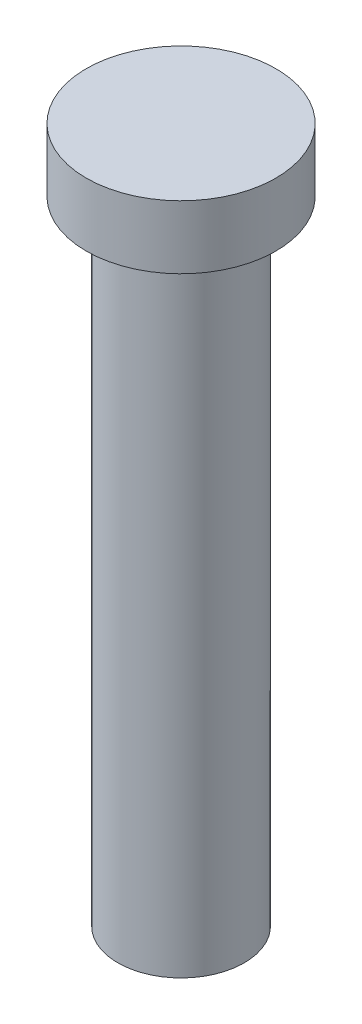
SolidWorks part; units mm, degrees
material "AISI 304"
ref_plane "前视基准面" through (0, 0, 0) normal (0, 0, 1) x (1, 0, 0)
ref_plane "上视基准面" through (0, 0, 0) normal (0, 1, 0) x (1, 0, 0)
ref_plane "右视基准面" through (0, 0, 0) normal (1, 0, 0) x (0, 0, -1)
other "Configuration Table"
sketch "草图1" plane through (0, 0, 0) normal (0, 1, 0) x (1, 0, 0)
  circle A0 centre (0, 0) radius 2.25
extrude "凸台-拉伸1" add sketch "草图1" along normal blind 1.5
sketch "草图2" plane through (0, 0, 0) normal (0, -1, 0) x (1, 0, 0)
  circle A0 centre (0, 0) radius 1.5
extrude "凸台-拉伸2" add sketch "草图2" along normal blind 15
